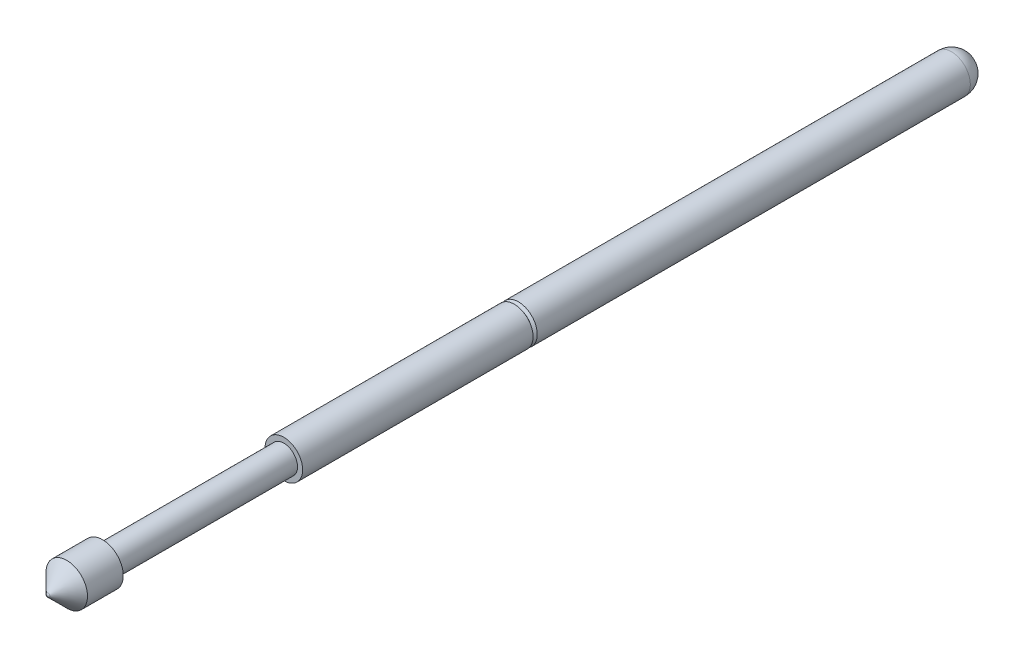
SolidWorks part; units mm, degrees
material "Золото без примесей"
ref_plane "Front" through (0, 0, 0) normal (0, 0, 1) x (1, 0, 0)
ref_plane "Top" through (0, 0, 0) normal (0, 1, 0) x (1, 0, 0)
ref_plane "Right" through (0, 0, 0) normal (1, 0, 0) x (0, 0, -1)
sketch "Эскиз1" plane through (0, 0, 0) normal (0, 1, 0) x (1, 0, 0)
  line L0 (0, 0) -> (0, -66.8671) construction
  line L1 (0, 0) -> (0, -33.35)
  line L3 (-0.75, -32.6414) -> (-0.75, -31.35)
  line L4 (-0.75, -31.35) -> (-0.495, -31.35)
  line L5 (-0.495, -31.35) -> (-0.495, -24.8)
  line L6 (-0.495, -24.8) -> (-0.68, -24.8)
  line L7 (-0.68, -24.8) -> (-0.68, -16.475)
  line L8 (-0.68, -16.475) -> (-0.5793, -16.4)
  line L9 (-0.5793, -16.4) -> (-0.68, -16.325)
  line L10 (-0.68, -16.325) -> (-0.68, -0.68)
  line L11 (-0.68, -16.325) -> (-0.68, -16.475) construction
  line L12 (-0.0707, -33.3207) -> (-0.75, -32.6414)
  arc A1 (-0.68, -0.68) -> (0, 0) centre (0, -0.68) cw
  arc A2 (0, -33.35) -> (-0.0707, -33.3207) centre (0, -33.25) cw
  point P16 (-0.68, -16.4)
  point P17 (-0.75, -32.5339)
  point P18 (0, 0)
  dimension "D5" = 33.35
  dimension "D2" = 0.1
  dimension "D1" = 1.36
  dimension "D3" = 1.5
  dimension "D4" = 2
  dimension "D6" = 45
  dimension "D7" = 6.55
  dimension "D8" = 0.99
  dimension "D9" = 0.15
  dimension "D10" = 8.4
revolve "Повернуть1" add sketch "Эскиз1" angle 360 about L0
